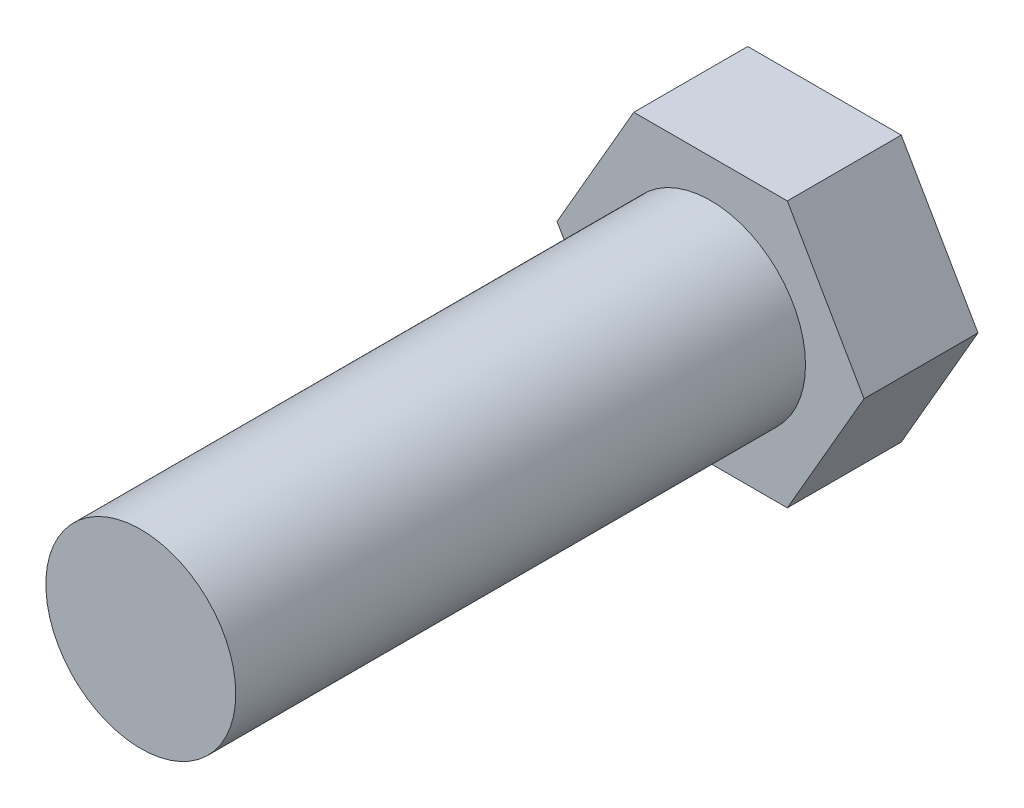
SolidWorks part; units mm, degrees
material "AISI Type A2 Tool Steel"
ref_plane "Front Plane" through (0, 0, 0) normal (0, 0, 1) x (1, 0, 0)
ref_plane "Top Plane" through (0, 0, 0) normal (0, 1, 0) x (1, 0, 0)
ref_plane "Right Plane" through (0, 0, 0) normal (1, 0, 0) x (0, 0, -1)
sketch "Sketch1" plane through (0, 0, 0) normal (0, 0, 1) x (1, 0, 0)
  line L1 (4.0415, 0) -> (2.0207, 3.5)
  line L2 (2.0207, 3.5) -> (-2.0207, 3.5)
  line L3 (-2.0207, 3.5) -> (-4.0415, 0)
  line L4 (-4.0415, 0) -> (-2.0207, -3.5)
  line L5 (-2.0207, -3.5) -> (2.0207, -3.5)
  line L6 (2.0207, -3.5) -> (4.0415, 0)
  circle A0 centre (0, 0) radius 3.5 construction
  dimension "D1" = 7
extrude "Boss-Extrude1" add sketch "Sketch1" along normal blind 3 contours L2 L3 L4 L5 L6 L1
sketch "Sketch2" plane through (0, 0, 3) normal (0, 0, 1) x (1, 0, 0)
  circle A0 centre (0, 0) radius 2.5
  dimension "D1" = 5
extrude "Boss-Extrude2" add sketch "Sketch2" along normal blind 15
